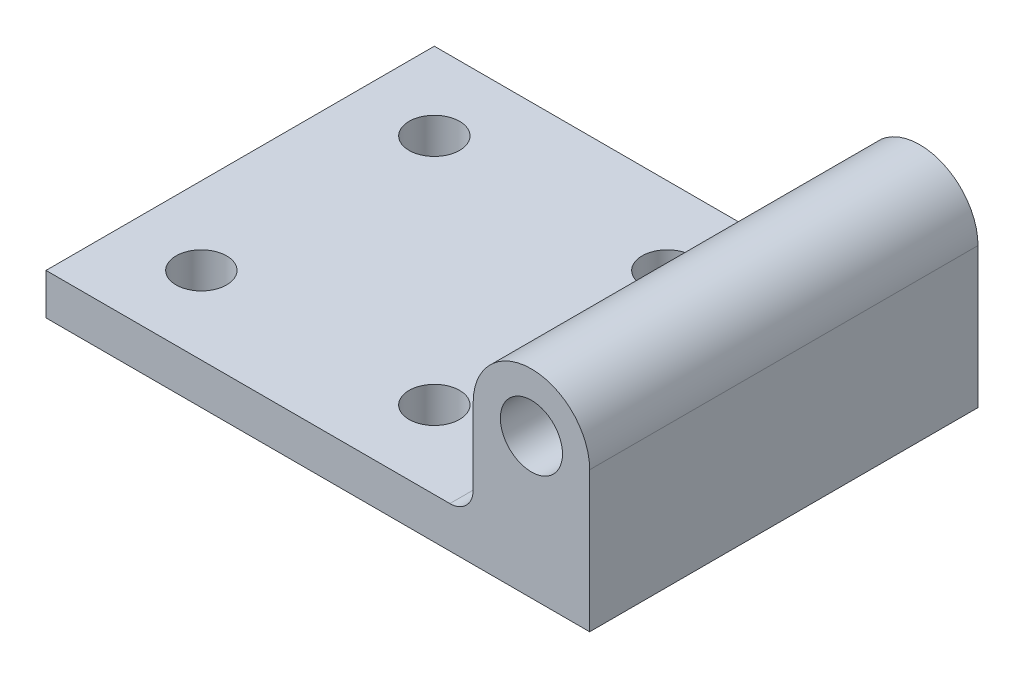
SolidWorks part; units mm, degrees
ref_plane "Front Plane" through (0, 0, 0) normal (0, 0, 1) x (1, 0, 0)
ref_plane "Top Plane" through (0, 0, 0) normal (0, 1, 0) x (1, 0, 0)
ref_plane "Right Plane" through (0, 0, 0) normal (1, 0, 0) x (0, 0, -1)
sketch "Sketch1" plane through (0, 0, 0) normal (0, 1, 0) x (1, 0, 0)
  line L0 (0, 0) -> (50, -50) construction
  line L1 (0, 0) -> (50, 0)
  line L2 (0, 0) -> (0, -50)
  line L3 (0, -50) -> (50, -50)
  line L4 (50, 0) -> (50, -50)
  line L5 (50, 0) -> (0, -50) construction
  line L6 (10, -10) -> (10, -40) construction
  line L7 (10, -40) -> (40, -40) construction
  line L8 (40, -40) -> (40, -10) construction
  line L9 (40, -10) -> (10, -10) construction
  line L10 (50, -50) -> (70, -50)
  line L11 (70, -50) -> (70, 0)
  line L12 (70, 0) -> (50, 0)
  circle A0 centre (10, -10) radius 3.25
  circle A1 centre (40, -10) radius 3.25
  circle A2 centre (40, -40) radius 3.25
  circle A3 centre (10, -40) radius 3.25
  dimension "D3" = 6.5
  dimension "D1" = 50
  dimension "D2" = 50
  dimension "D4" = 30
  dimension "D5" = 20
extrude "Boss-Extrude1" add sketch "Sketch1" along normal blind 5.3 contours L4 L1 L2 L3 A3 A2 A1 A0 | L11 L12 L4 L10
sketch "Sketch2" plane through (0, 0, 50) normal (0, 0, 1) x (1, 0, 0)
  line L0 (55, 18.0714) -> (55, 5.3)
  line L1 (0, 5.3) -> (70, 5.3) construction
  line L2 (55, 5.3) -> (70, 5.3)
  line L3 (70, 5.3) -> (70, 18.0714)
  circle A0 centre (62.5, 18.0714) radius 4
  arc A1 (70, 18.0714) -> (55, 18.0714) centre (62.5, 18.0714) ccw
  dimension "D1" = 8
  dimension "D2" = 15
extrude "Boss-Extrude2" add sketch "Sketch2" against normal up to surface (50 mm away) up to face at (35, 2.65, 0)
fillet "Fillet1" radius 3 1 edges at (55, 5.3, 25)
